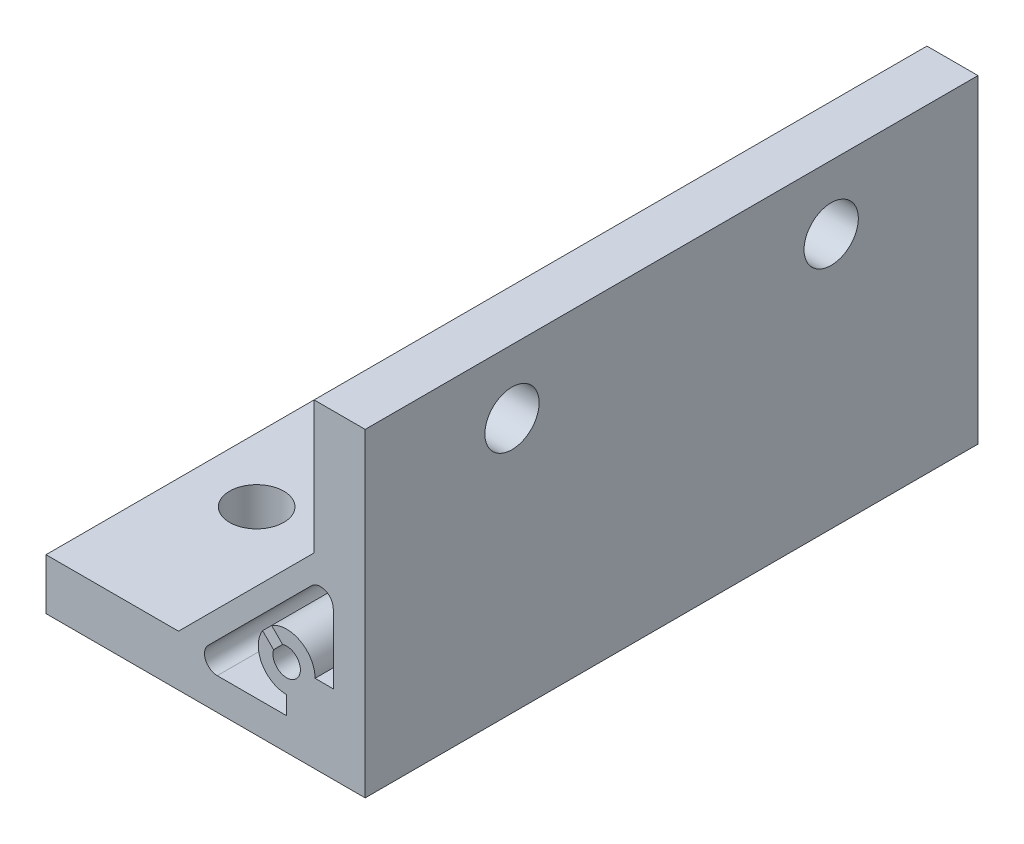
SolidWorks part; units mm, degrees
ref_plane "前视基准面" through (0, 0, 0) normal (0, 0, 1) x (1, 0, 0)
ref_plane "上视基准面" through (0, 0, 0) normal (0, 1, 0) x (1, 0, 0)
ref_plane "右视基准面" through (0, 0, 0) normal (1, 0, 0) x (0, 0, -1)
sketch "草图1" plane through (0, 0, 0) normal (0, 0, 1) x (1, 0, 0)
  line B0 (0, 0) -> (50, 0)
  line B1 (50, 0) -> (50, 50)
  line B2 (0, 8) -> (20.7574, 8)
  line B3 (42, 29.2426) -> (42, 50)
  line B4 (0, 8) -> (0, 0)
  line B5 (42, 50) -> (50, 50)
  line B6 (37.0613, 14.3529) -> (35.341, 16.0733)
  line B7 (35.6471, 12.9387) -> (33.9267, 14.659)
  line B8 (25.4142, 8.4142) -> (41.5858, 24.5858)
  line B9 (20.7574, 8) -> (42, 29.2426)
  line B10 (26.8284, 5) -> (37.7, 5)
  line B11 (45, 23.1716) -> (45, 12.3)
  line B12 (37.7, 5) -> (37.7, 7.85)
  line B13 (42.15, 12.3) -> (45, 12.3)
  arc B14 (33.9267, 14.659) -> (37.7, 7.85) centre (37.7, 12.3) ccw
  arc B15 (42.15, 12.3) -> (35.341, 16.0733) centre (37.7, 12.3) ccw
  arc B16 (35.6471, 12.9387) -> (37.0613, 14.3529) centre (37.7, 12.3) ccw
  arc B17 (25.4142, 8.4142) -> (26.8284, 5) centre (26.8284, 7) ccw
  arc B18 (45, 23.1716) -> (41.5858, 24.5858) centre (43, 23.1716) ccw
sketch_block_instance "A$C19004297-1"
sketch_block "A$C19004297"
extrude "凸台-拉伸1" add sketch "草图1" along normal mid plane 96
sketch "草图3" plane through (0, 8, 0) normal (0, 1, 0) x (1, 0, 0)
  line L0 (0, 0) -> (19.5129, 0) construction
  line L1 (0, -48) -> (0, 48) construction
  circle A0 centre (10, 25) radius 4.25
  circle A1 centre (10, -25) radius 4.25
  dimension "D1" = 10
  dimension "D2" = 25
extrude "切除-拉伸1" cut sketch "草图3" against normal through all
sketch "草图4" plane through (6.3787, -6.3787, 0) normal (-0.7071, 0.7071, 0) x (0, 0, 1)
  line L0 (48, 35.3553) -> (-48, 35.3553) construction
  line L1 (48, 50.3762) -> (48, 20.3345) construction
  line L2 (-48, 50.3762) -> (-48, 20.3345) construction
ref_plane "基准面2" through (25, 25, 0) normal (-0.7071, -0.7071, 0) x (0, 0, 1)
mirror "镜向1" about plane through (25, 25, 0) normal (-0.7071, -0.7071, 0) of "切除-拉伸1"
